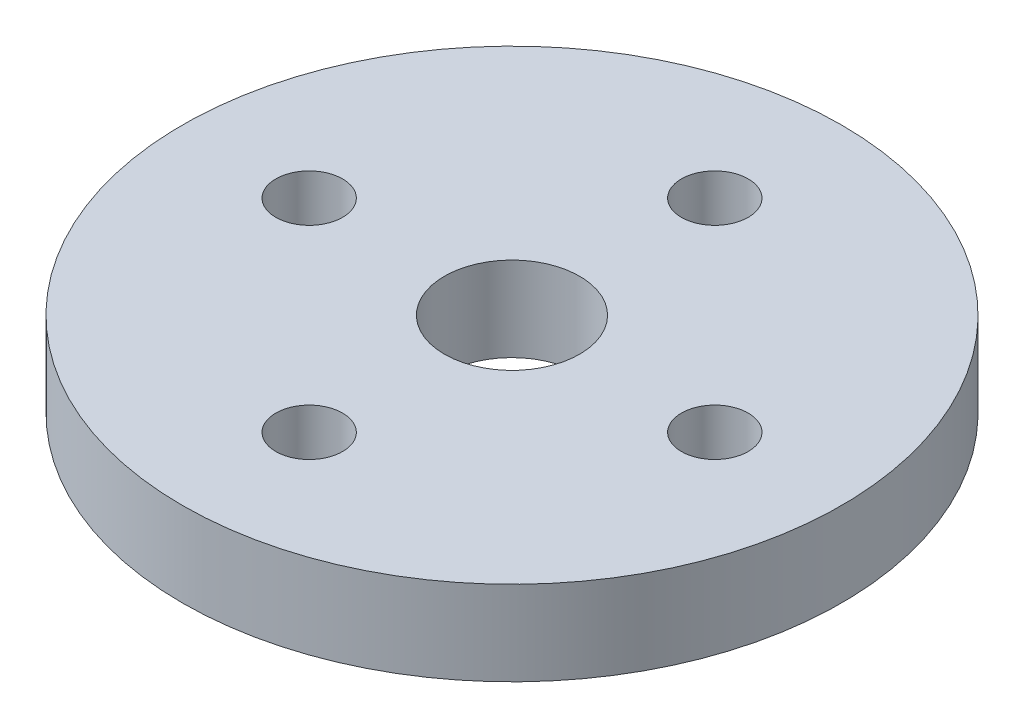
SolidWorks part; units mm, degrees
ref_plane "Front Plane" through (0, 0, 0) normal (0, 0, 1) x (1, 0, 0)
ref_plane "Top Plane" through (0, 0, 0) normal (0, 1, 0) x (1, 0, 0)
ref_plane "Right Plane" through (0, 0, 0) normal (1, 0, 0) x (0, 0, -1)
sketch "Sketch1" plane through (0, 0, 0) normal (0, 1, 0) x (1, 0, 0)
  line L0 (0, 19.5) -> (0, -19.5) construction
  line L1 (-19.5, 0) -> (19.5, 0) construction
  circle A0 centre (0, 0) radius 19.5
  circle A1 centre (0, 0) radius 4
  circle A2 centre (0, 12) radius 1.975
  circle A3 centre (12, 0) radius 1.975
  circle A4 centre (0, -12) radius 1.975
  circle A5 centre (-12, 0) radius 1.975
  point P19 (0, 0)
  dimension "D1" = 39
  dimension "D2" = 12
  dimension "D3" = 3.95
  dimension "D4" = 8
  dimension "D5" = 4
extrude "Boss-Extrude1" add sketch "Sketch1" along normal blind 5
